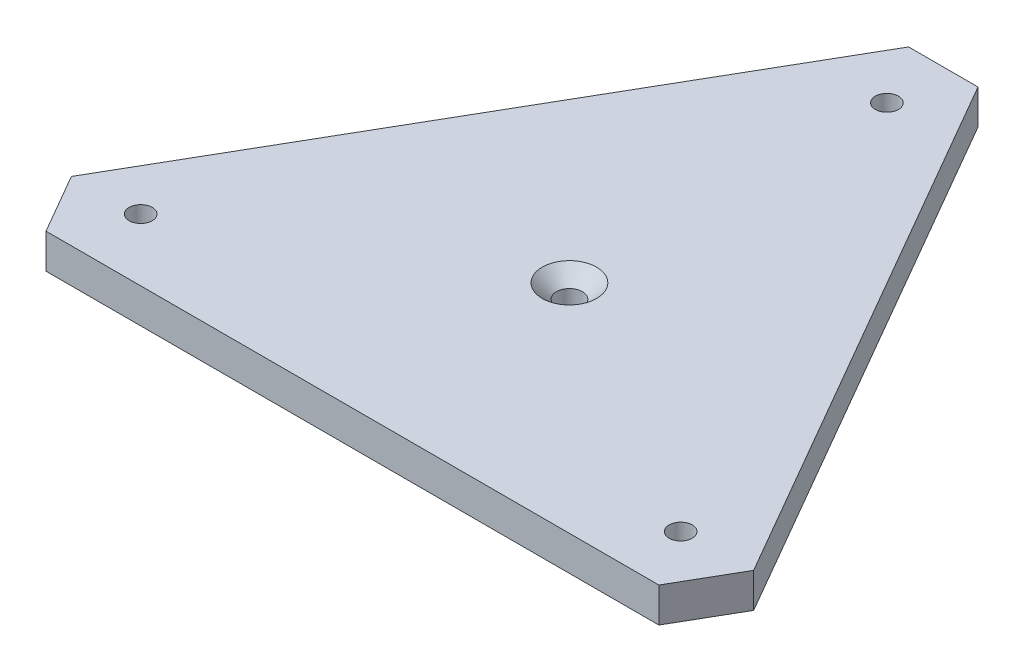
SolidWorks part; units mm, degrees
ref_plane "Front Plane" through (0, 0, 0) normal (0, 0, 1) x (1, 0, 0)
ref_plane "Top Plane" through (0, 0, 0) normal (0, 1, 0) x (1, 0, 0)
ref_plane "Right Plane" through (0, 0, 0) normal (1, 0, 0) x (0, 0, -1)
sketch "Sketch2" plane through (0, 0, 0) normal (0, 1, 0) x (1, 0, 0)
  line L0 (-65, -37.5278) -> (-59, -27.1355)
  line L1 (0, 75.0555) -> (-65, -37.5278)
  line L2 (-65, -37.5278) -> (65, -37.5278)
  line L3 (65, -37.5278) -> (0, 75.0555)
  line L4 (6, 64.6632) -> (-6, 64.6632)
  line L5 (-59, -27.1355) -> (-53, -37.5278)
  line L6 (53, -37.5278) -> (59, -27.1355)
  circle A0 centre (0, 0) radius 37.5278 construction
  point P15 (0, 0)
  dimension "D1" = 130
  dimension "D2" = 12
  dimension "D3" = 60
  dimension "D4" = 3
extrude "Boss-Extrude1" add sketch "Sketch2" along normal blind 6 contours L2 L6 L3 L4 L1 L5
sketch "Sketch3" plane through (0, 6, 0) normal (0, 1, 0) x (1, 0, 0)
  line L0 (-59, -27.1355) -> (-40.8135, -16.6355)
  line L1 (-59, -27.1355) -> (-53, -37.5278) construction
  line L2 (-53, -37.5278) -> (-34.8135, -27.0278)
  line L3 (-40.8135, -16.6355) -> (-34.8135, -27.0278)
  line L4 (-38.0606, -21.4036) -> (-47.3727, -26.78)
  circle A0 centre (-47.3727, -26.78) radius 2
  circle A5 centre (0.4942, 54.416) radius 2
  circle A6 centre (46.8785, -27.636) radius 2
  point P18 (0, 0)
  dimension "D5" = 3
  dimension "D1" = 90
  dimension "D2" = 90
  dimension "D3" = 21
  dimension "D4" = 10.7528
sketch "Sketch5" plane through (0, 6, 0) normal (0, 1, 0) x (1, 0, 0)
  circle A0 centre (0, 0) radius 2
  point P0 (0, 0)
hole_wizard "CSK for M4 Flat Head Machine Screw1" positions "Sketch5" profile "Sketch6" countersink size "M4" standard "ANSI Metric" end condition through all
sketch "Sketch6" plane through (0, 6, 0) normal (1, 0, 0) x (0, 0, 1)
  line L0 (0, 0) -> (0, 6)
  line L1 (0, 6) -> (2.25, 6)
  line L2 (2.25, 6) -> (2.25, 2.45)
  line L3 (2.25, 2.45) -> (4.7, 0)
  line L5 (4.7, 0) -> (0, 0)
  line L6 (-2.25, 2.45) -> (-4.7, 0) construction
  line L11 (0, -6.35) -> (0, 107.95) construction
  dimension "Thru Hole Dia." = 4.5
  dimension "Thru Hole Depth" = 6
  dimension "Near C'Sink Dia." = 9.4
  dimension "Near C'Sink Angle" = 90
extrude "Cut-Extrude1" cut sketch "Sketch3" against normal through all both and the other way through all
sketch "Sketch7" plane through (0, 6, 0) normal (0, 1, 0) x (1, 0, 0)
  line L1 (-43.7756, -25.1365) -> (-46.9975, -22.843)
  line L2 (-46.9975, -22.843) -> (-50.5947, -24.4865)
  line L3 (-50.5947, -24.4865) -> (-50.9699, -28.4235)
  line L4 (-50.9699, -28.4235) -> (-47.748, -30.717)
  line L5 (-47.748, -30.717) -> (-44.1508, -29.0735)
  line L6 (-44.1508, -29.0735) -> (-43.7756, -25.1365)
  line L18 (3.7161, 52.1225) -> (4.0914, 56.0595)
  line L19 (0.1189, 50.479) -> (3.7161, 52.1225)
  line L20 (-3.103, 52.7725) -> (0.1189, 50.479)
  line L21 (-2.7277, 56.7095) -> (-3.103, 52.7725)
  line L22 (0.8695, 58.353) -> (-2.7277, 56.7095)
  line L23 (4.0914, 56.0595) -> (0.8695, 58.353)
  line L24 (43.2814, -29.2795) -> (46.5033, -31.573)
  line L25 (43.6566, -25.3425) -> (43.2814, -29.2795)
  line L26 (47.2538, -23.699) -> (43.6566, -25.3425)
  line L27 (50.4757, -25.9925) -> (47.2538, -23.699)
  line L28 (50.1005, -29.9295) -> (50.4757, -25.9925)
  line L29 (46.5033, -31.573) -> (50.1005, -29.9295)
  circle A0 centre (-47.3727, -26.78) radius 3.425 construction
  point P24 (0, 0)
  dimension "D1" = 6.85
  dimension "D2" = 3
extrude "Cut-Extrude3" cut sketch "Sketch7" against normal blind 10 from offset 3
